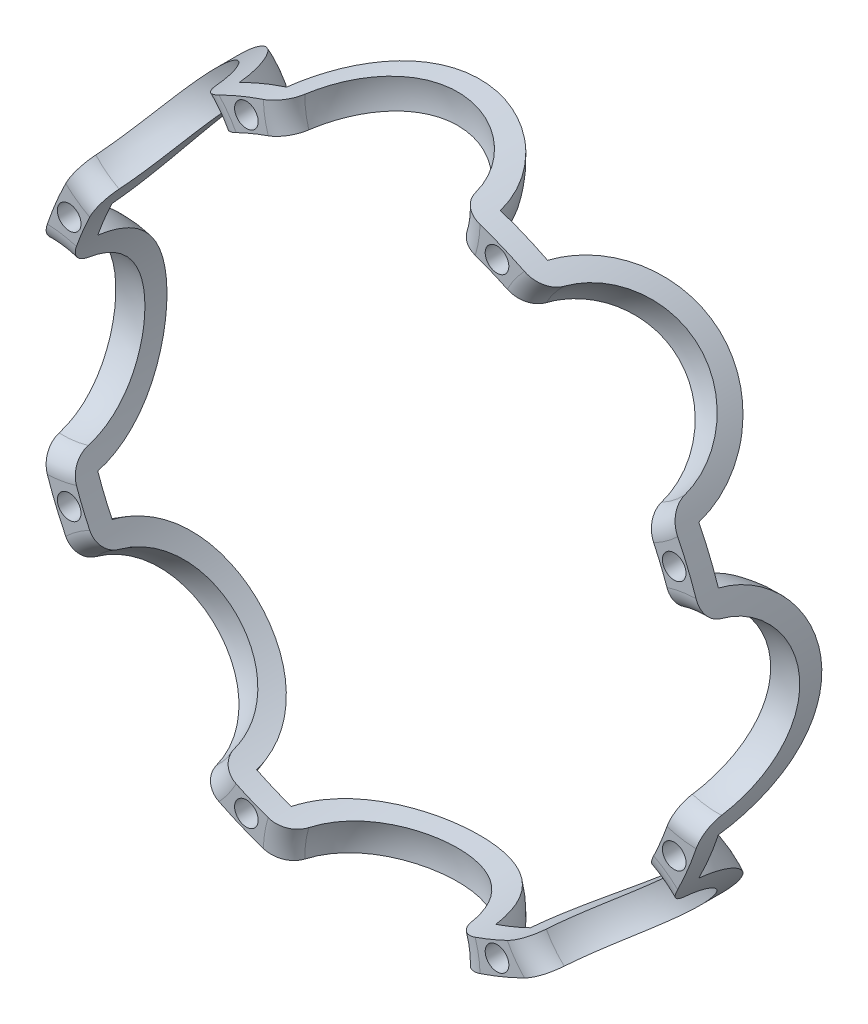
SolidWorks part; units mm, degrees
ref_plane "Front Plane" through (0, 0, 0) normal (0, 0, 1) x (1, 0, 0)
ref_plane "Top Plane" through (0, 0, 0) normal (0, 1, 0) x (1, 0, 0)
ref_plane "Right Plane" through (0, 0, 0) normal (1, 0, 0) x (0, 0, -1)
sketch "Sketch1" plane through (0, 0, 0) normal (0, 0, 1) x (1, 0, 0)
  circle A0 centre (0, 0) radius 14.4615
  circle A1 centre (0, 0) radius 13.2308
  dimension "D1" = 28.9231
  dimension "D2" = 26.4615
extrude "Boss-Extrude1" add sketch "Sketch1" along normal blind 9.8462
sketch "Sketch2" plane through (0, 0, 9.8462) normal (0, 0, 1) x (1, 0, 0)
  line L0 (0, 17.5385) -> (0, 10.1538)
  circle A0 centre (0, 0) radius 13.8462 construction
  arc A1 (0, 10.1538) -> (0, 17.5385) centre (0, 13.8462) ccw
  dimension "D1" = 27.6923
  dimension "D2" = 7.3846
revolve "Cut-Revolve1" cut sketch "Sketch2" angle 360 about L0
pattern_circular "CirPattern1" count 8 over 360 about axis through (0, 0, 0) along (0, 0, 1) of "Cut-Revolve1"
shell "Shell1" thickness 0.9231
sketch "Sketch3" plane through (0, 0, 9.8462) normal (0, 0, 1) x (1, 0, 0)
  line L0 (0, 0) -> (5.2987, 12.7922) construction
  line L1 (0, 12.1317) -> (0, 17.275) construction
  circle A0 centre (0, 0) radius 13.8462 construction
  circle A1 centre (5.2987, 12.7922) radius 0.5
  circle A2 centre (12.7922, 5.2987) radius 0.5
  circle A3 centre (12.7922, -5.2987) radius 0.5
  circle A4 centre (5.2987, -12.7922) radius 0.5
  circle A5 centre (-5.2987, -12.7922) radius 0.5
  circle A6 centre (-12.7922, -5.2987) radius 0.5
  circle A7 centre (-12.7922, 5.2987) radius 0.5
  circle A8 centre (-5.2987, 12.7922) radius 0.5
  point P24 (0, 0)
  dimension "D1" = 27.6923
  dimension "D2" = 1
  dimension "D3" = 22.5
  dimension "D4" = 8
extrude "Cut-Extrude1" cut sketch "Sketch3" against normal blind 9.8462
fillet "Fillet1" radius 1 16 edges at (-12.0356, -6.8592, 9.8462) (-6.8592, -12.0356, 9.8462) (-13.3606, 3.6602, 9.8462) (-13.3606, -3.6602, 9.8462) (-6.8592, 12.0356, 9.8462) (-12.0356, 6.8592, 9.8462) (-3.6602, 13.3606, 9.8462) (3.6602, 13.3606, 9.8462) (6.8592, 12.0356, 9.8462) (12.0356, 6.8592, 9.8462) (13.3606, 3.6602, 9.8462) (13.3606, -3.6602, 9.8462) (12.0356, -6.8592, 9.8462) (6.8592, -12.0356, 9.8462) (3.6602, -13.3606, 9.8462) (-3.6602, -13.3606, 9.8462)
